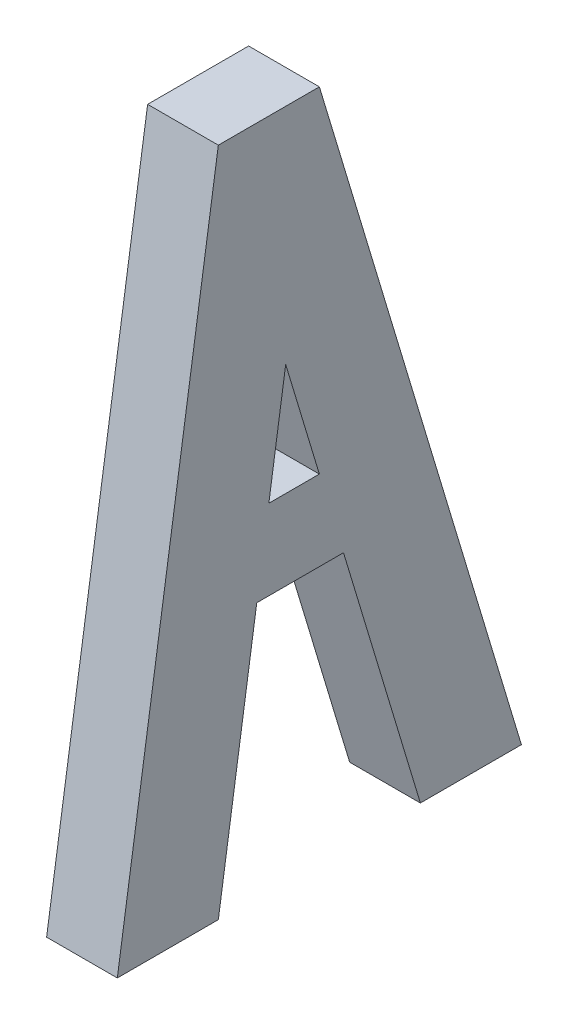
SolidWorks part; units mm, degrees
ref_plane "Alzado" through (0, 0, 0) normal (0, 0, 1) x (1, 0, 0)
ref_plane "Planta" through (0, 0, 0) normal (0, 1, 0) x (1, 0, 0)
ref_plane "Vista lateral" through (0, 0, 0) normal (1, 0, 0) x (0, 0, -1)
sketch "Croquis3" plane through (0, 0, 0) normal (1, 0, 0) x (0, 0, -1)
  line L6 (-73.801, -80.6247) -> (-123.801, -80.6247)
  line L7 (-123.801, -80.6247) -> (-73.801, 251.3653)
  line L8 (-73.801, 251.3653) -> (-23.801, 251.3653)
  line L9 (-73.801, -80.6247) -> (-23.801, 251.3653)
  line L12 (-23.801, 251.3653) -> (76.199, -80.6247)
  line L13 (76.199, -80.6247) -> (26.199, -80.6247)
  line L14 (26.199, -80.6247) -> (-40.4676, 140.7019)
  line L15 (-40.4676, 140.7019) -> (-23.801, 251.3653)
  line L16 (-48.801, 85.3703) -> (-54.7755, 45.7004)
  line L17 (-54.7755, 45.7004) -> (-11.8519, 45.7004)
  line L18 (-11.8519, 45.7004) -> (-23.801, 85.3703)
  line L19 (-23.801, 85.3703) -> (-48.801, 85.3703)
  dimension "D1" = 50
  dimension "D2" = 50
  dimension "D4" = 50
  dimension "D5" = 100
extrude "Saliente-Extruir1" add sketch "Croquis3" along normal blind 35 contours L6 L9 L8 L7 | L14 L19 L9 L17 | L14 L13 L12 L9
